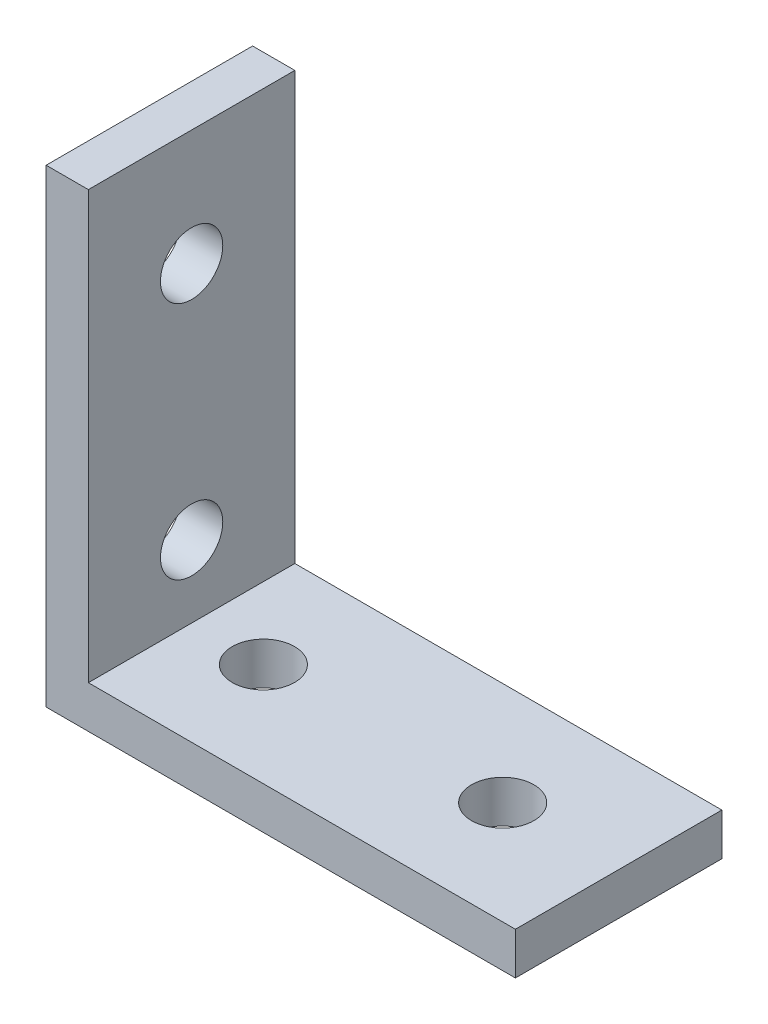
SolidWorks part; units mm, degrees
ref_plane "Front Plane" through (0, 0, 0) normal (0, 0, 1) x (1, 0, 0)
ref_plane "Top Plane" through (0, 0, 0) normal (0, 1, 0) x (1, 0, 0)
ref_plane "Right Plane" through (0, 0, 0) normal (1, 0, 0) x (0, 0, -1)
sketch "Sketch1" plane through (0, 0, 0) normal (0, 1, 0) x (1, 0, 0)
  line L1 (0, 0) -> (50.8, 0)
  line L2 (0, 0) -> (0, 22.352)
  line L3 (0, 22.352) -> (50.8, 22.352)
  line L4 (50.8, 0) -> (50.8, 22.352)
  dimension "D1" = 50.8
  dimension "D2" = 22.352
extrude "Boss-Extrude1" add sketch "Sketch1" along normal blind 50.8
sketch "Sketch2" plane through (0, 0, 0) normal (0, 0, 1) x (1, 0, 0)
  line L5 (4.572, 4.572) -> (50.8, 4.572)
  line L6 (4.572, 50.8) -> (4.572, 4.572)
  line L7 (4.572, 4.572) -> (50.8, 4.572)
  line L8 (4.572, 50.8) -> (4.572, 4.572)
  dimension "D1" = 4.572
extrude "Cut-Extrude2" cut sketch "Sketch2" against normal through all and the other way through all
hole_wizard "17/64 (0.26563) Diameter Hole1" positions "3DSketch1" profile "Sketch3" hole size "17/64" standard "ANSI Inch" end condition through all
sketch3d "3DSketch1"
  line L9 (0, 0, -11.176) -> (12.3432, 0, -11.176)
  line L10 (0, 0, -22.352) -> (0, 0, 0) construction
  line L12 (0, 0, -11.176) -> (0, 12.3745, -11.176)
  point P0 (4.572, 12.3745, -11.176)
  point P2 (4.572, 38.2786, -11.176)
  point P4 (12.3432, 4.572, -11.176)
  point P6 (38.25, 4.572, -11.176)
  point P46 (4.572, 12.3556, -11.176)
  point P47 (4.572, 12.3745, -11.176)
  point P48 (4.572, 12.3745, -11.176)
sketch "Sketch3" plane through (4.572, 12.3745, -11.176) normal (0, 1, 0) x (0, 0, -1)
  line L0 (0, 0) -> (0, 4.572)
  line L1 (0, 4.572) -> (3.3735, 4.572)
  line L2 (3.3735, 4.572) -> (3.3735, 0)
  line L5 (3.3735, 0) -> (0, 0)
  line L11 (0, -6.35) -> (0, 107.95) construction
  dimension "Thru Hole Dia." = 6.747
  dimension "Thru Hole Depth" = 4.572
